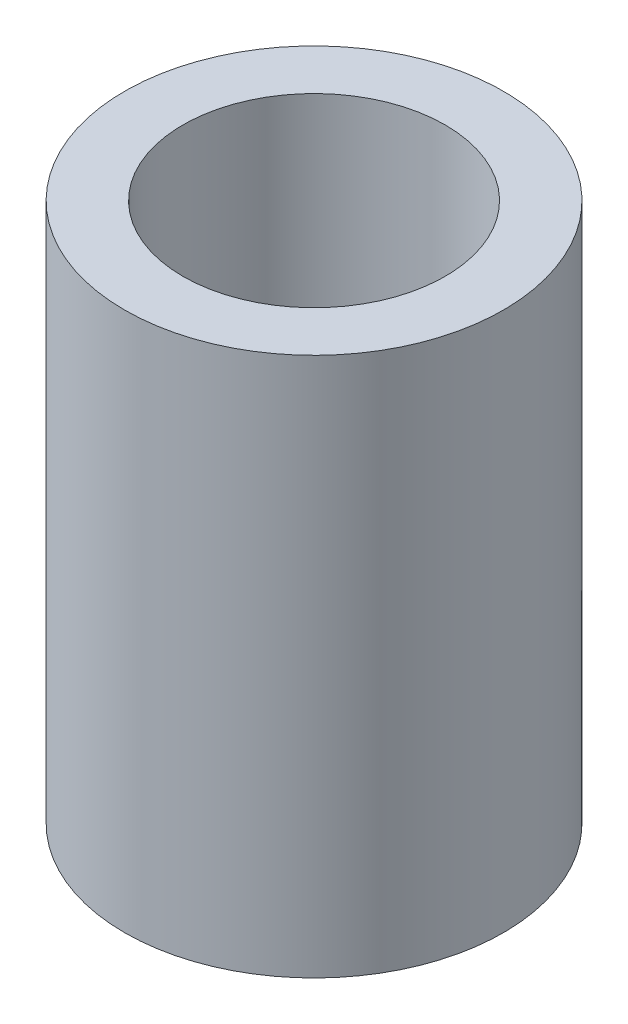
SolidWorks part; units mm, degrees
ref_plane "Alzado" through (0, 0, 0) normal (0, 0, 1) x (1, 0, 0)
ref_plane "Planta" through (0, 0, 0) normal (0, 1, 0) x (1, 0, 0)
ref_plane "Vista lateral" through (0, 0, 0) normal (1, 0, 0) x (0, 0, -1)
sketch "Croquis1" plane through (0, 0, 0) normal (0, 1, 0) x (1, 0, 0)
  circle A0 centre (0, 0) radius 4.5
  circle A1 centre (0, 0) radius 6.5
  dimension "D1" = 2
extrude "Saliente-Extruir1" add sketch "Croquis1" along normal blind 18.5
